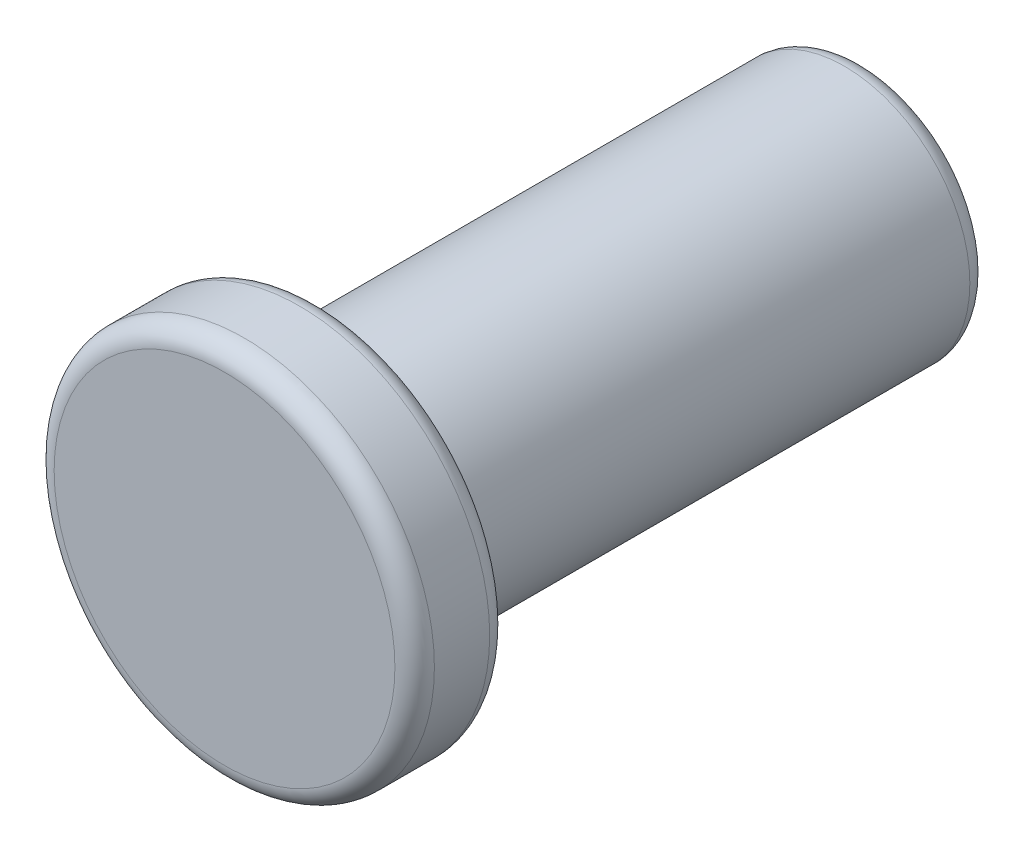
SolidWorks part; units mm, degrees
ref_plane "Front Plane" through (0, 0, 0) normal (1, 0, 0) x (0, 1, 0)
ref_plane "Top Plane" through (0, 0, 0) normal (0, 0, 1) x (0, 1, 0)
ref_plane "Right Plane" through (0, 0, 0) normal (0, 1, 0) x (-1, 0, 0)
sketch "Sketch1" plane through (0, 0, 0) normal (1, 0, 0) x (0, 1, 0)
  line L0 (0, 0) -> (4.815, 0)
  line L1 (4.815, 0) -> (4.815, -2.4)
  line L2 (4.815, -2.4) -> (3.175, -2.4)
  line L3 (3.175, -2.4) -> (3.175, -53.2)
  line L4 (3.175, -53.2) -> (0, -53.2)
  line L5 (0, -53.2) -> (0, 0)
  line L6 (0, -335.5768) -> (0, 16305.0472) construction
  dimension "D1" = 6.35
  dimension "D2" = 50.8
  dimension "D3" = 1.64
  dimension "D4" = 2.4
revolve "Revolve1" add sketch "Sketch1" angle 360 about L6
sketch "Sketch2" plane through (0, 0, 0) normal (1, 0, 0) x (0, 1, 0)
  line L0 (0, -47.7) -> (0, -42.1) construction
  line L1 (0, -42.1) -> (0, -36.5) construction
  line L2 (0, -36.5) -> (0, -30.9) construction
  line L3 (0, -30.9) -> (0, -25.3) construction
  line L4 (0, -25.3) -> (0, -19.7) construction
  line L5 (0, -47.7) -> (0, -49) construction
  line L6 (-3.175, -53.2) -> (3.175, -53.2) construction
  circle A0 centre (0, -47.7) radius 1.3
  circle A1 centre (0, -42.1) radius 1.3
  circle A3 centre (0, -25.3) radius 1.3
  circle A4 centre (0, -30.9) radius 1.3
  circle A6 centre (0, -36.5) radius 1.3
  circle A7 centre (0, -19.7) radius 1.3
  point P11 (0, -46.4)
  point P14 (0, -43.4)
  dimension "D1" = 2.6
  dimension "D2" = 4.2
  dimension "D3" = 3
extrude "Cut-Extrude1" cut sketch "Sketch2" against normal through all both and the other way through all
fillet "f7f" radius 0.5 2 edges at (-4.815, 0, -2.4) (-4.815, 0, 0)
sketch "Sketch3" plane through (0, 0, 0) normal (1, 0, 0) x (0, 1, 0)
  line L0 (3.175, -53.2) -> (3.175, -2.4) construction
  line L1 (-3.175, -53.2) -> (3.175, -53.2)
  line L2 (-3.175, -53.2) -> (-3.175, -16.2)
  line L3 (-3.175, -16.2) -> (3.175, -16.2)
  line L4 (3.175, -53.2) -> (3.175, -16.2)
  dimension "D1" = 37
extrude "Cut-Extrude2" cut sketch "Sketch3" against normal through all both and the other way through all
fillet "Fillet1" radius 0.5 1 edges at (3.175, 0, -16.2)
